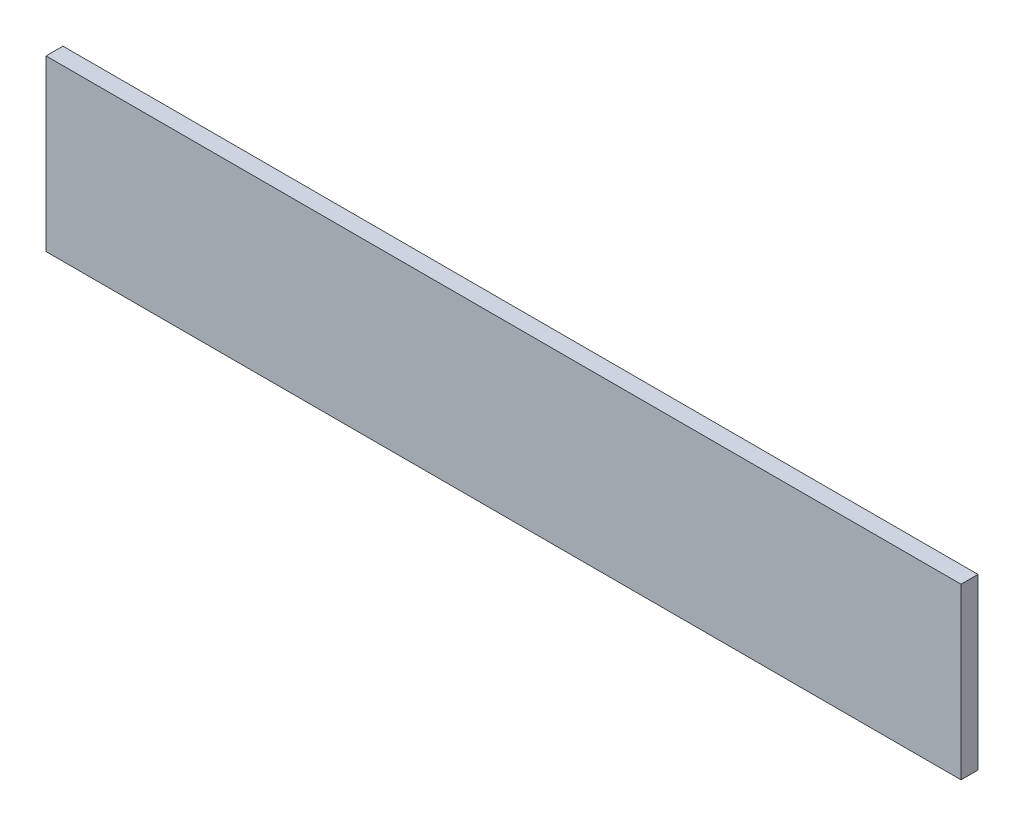
SolidWorks part; units mm, degrees
ref_plane "Front Plane" through (0, 0, 0) normal (0, 0, 1) x (1, 0, 0)
ref_plane "Top Plane" through (0, 0, 0) normal (0, 1, 0) x (1, 0, 0)
ref_plane "Right Plane" through (0, 0, 0) normal (1, 0, 0) x (0, 0, -1)
sketch "Sketch1" plane through (0, 0, 0) normal (0, 0, 1) x (1, 0, 0)
  line L1 (0, 0) -> (540, 0)
  line L2 (0, 0) -> (0, 100)
  line L3 (0, 100) -> (540, 100)
  line L4 (540, 0) -> (540, 100)
  dimension "D1" = 540
  dimension "D2" = 100
extrude "Boss-Extrude1" add sketch "Sketch1" along normal blind 10
